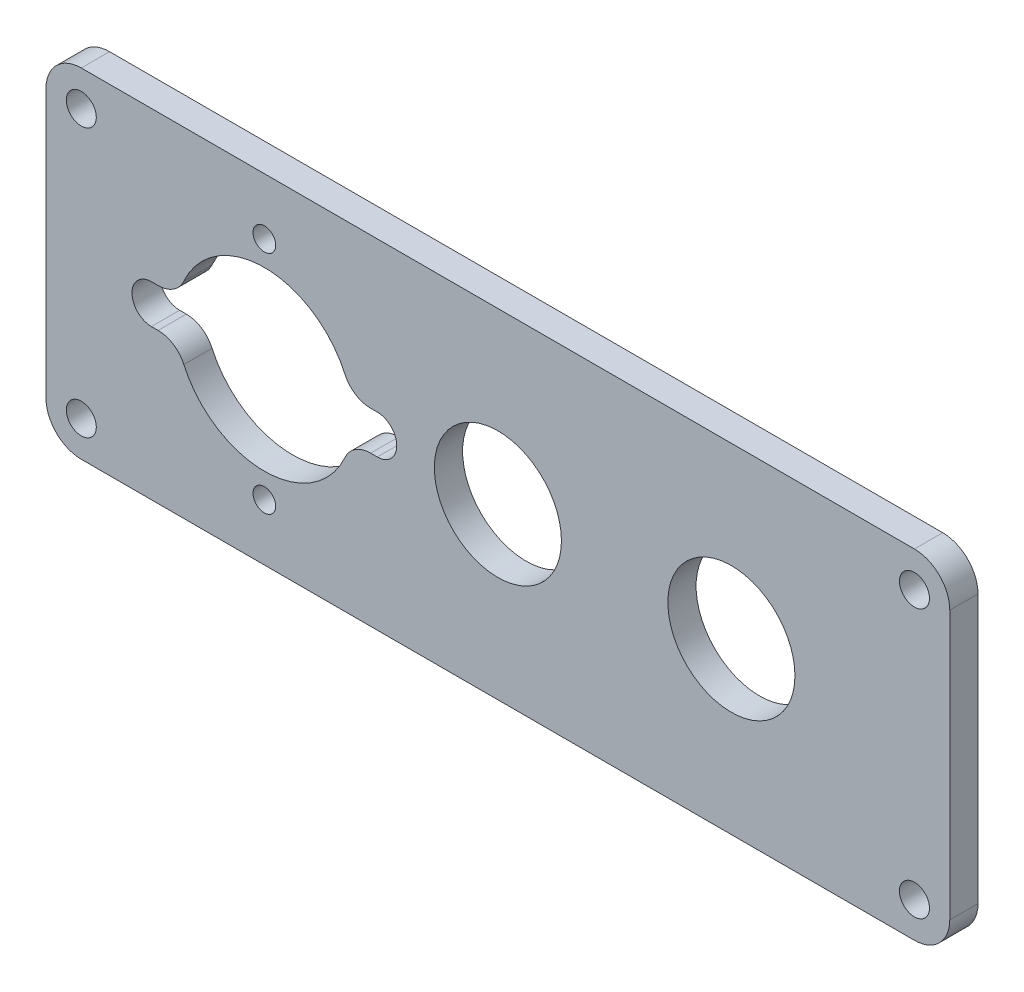
SolidWorks part; units mm, degrees
ref_plane "Front Plane" through (0, 0, 0) normal (0, 0, 1) x (1, 0, 0)
ref_plane "Top Plane" through (0, 0, 0) normal (0, 1, 0) x (1, 0, 0)
ref_plane "Right Plane" through (0, 0, 0) normal (1, 0, 0) x (0, 0, -1)
sketch "Sketch1" plane through (0, 0, 0) normal (0, 0, 1) x (1, 0, 0)
  line L0 (-28.6016, 4.3688) -> (-27.1018, 4.3688)
  line L1 (-93.6625, -38.1) -> (93.6625, -38.1)
  line L2 (-101.6, -30.1625) -> (-101.6, 30.1625)
  line L3 (-93.6625, 38.1) -> (93.6625, 38.1)
  line L4 (101.6, -30.1625) -> (101.6, 30.1625)
  line L5 (-101.6, -38.1) -> (101.6, 38.1) construction
  line L6 (-101.6, 38.1) -> (101.6, -38.1) construction
  line L7 (-93.6625, -30.1625) -> (93.6625, -30.1625) construction
  line L8 (-93.6625, -30.1625) -> (-93.6625, 30.1625) construction
  line L9 (-93.6625, 30.1625) -> (93.6625, 30.1625) construction
  line L10 (93.6625, -30.1625) -> (93.6625, 30.1625) construction
  line L11 (-93.6625, -30.1625) -> (93.6625, 30.1625) construction
  line L12 (-93.6625, 30.1625) -> (93.6625, -30.1625) construction
  line L13 (-77.9018, 0) -> (-52.5018, -25.4) construction
  line L14 (-77.9018, 0) -> (-52.5018, 25.4) construction
  line L15 (-52.5018, 25.4) -> (-27.1018, 0) construction
  line L16 (-52.5018, -25.4) -> (-27.1018, 0) construction
  line L17 (-77.9018, 0) -> (-27.1018, 0) construction
  line L18 (-52.5018, 25.4) -> (-52.5018, -25.4) construction
  line L19 (-27.1018, -4.3688) -> (-28.6016, -4.3688)
  line L20 (-76.402, 4.3688) -> (-77.9018, 4.3688)
  line L21 (-76.402, -4.3688) -> (-77.9018, -4.3688)
  circle A0 centre (0, 0) radius 14.2875
  circle A1 centre (52.5018, 0) radius 14.2875
  circle A2 centre (-52.5018, 0) radius 14.2875 construction
  circle A3 centre (-93.6625, 30.1625) radius 3.3734
  circle A4 centre (93.6625, 30.1625) radius 3.3734
  circle A5 centre (93.6625, -30.1625) radius 3.3734
  circle A6 centre (-93.6625, -30.1625) radius 3.3734
  arc A7 (-93.6625, -38.1) -> (-101.6, -30.1625) centre (-93.6625, -30.1625) cw
  arc A8 (93.6625, -38.1) -> (101.6, -30.1625) centre (93.6625, -30.1625) ccw
  arc A9 (93.6625, 38.1) -> (101.6, 30.1625) centre (93.6625, 30.1625) cw
  arc A10 (-101.6, 30.1625) -> (-93.6625, 38.1) centre (-93.6625, 30.1625) cw
  arc A11 (-34.3956, 8.1203) -> (-70.608, 8.1203) centre (-52.5018, 0) ccw
  circle A12 centre (-52.5018, 25.4) radius 2.5527
  arc A13 (-27.1018, -4.3688) -> (-27.1018, 4.3688) centre (-27.1018, 0) ccw
  circle A14 centre (-52.5018, -25.4) radius 2.5527
  arc A15 (-77.9018, 4.3688) -> (-77.9018, -4.3688) centre (-77.9018, 0) ccw
  arc A16 (-28.6016, -4.3688) -> (-34.3956, -8.1203) centre (-28.6016, -10.7188) ccw
  arc A17 (-28.6016, 4.3688) -> (-34.3956, 8.1203) centre (-28.6016, 10.7188) cw
  arc A18 (-70.608, -8.1203) -> (-34.3956, -8.1203) centre (-52.5018, 0) ccw
  arc A19 (-76.402, -4.3688) -> (-70.608, -8.1203) centre (-76.402, -10.7188) cw
  arc A20 (-76.402, 4.3688) -> (-70.608, 8.1203) centre (-76.402, 10.7188) ccw
  point P51 (-71.8587, -4.3688)
  dimension "D3" = 28.575
  dimension "D8" = 6.7469
  dimension "D9" = 7.9375
  dimension "D10" = 39.6875
  dimension "D11" = 8.7376
  dimension "D12" = 5.1054
  dimension "D14" = 6.35
  dimension "D15" = 6.35
  dimension "D2" = 52.5018
  dimension "D1" = 52.5018
  dimension "D4" = 187.325
  dimension "D5" = 60.325
  dimension "D6" = 76.2
  dimension "D7" = 203.2
  dimension "D13" = 50.8
extrude "Boss-Extrude1" add sketch "Sketch1" along normal blind 6.35
equation "\"D1@Sketch1\"=\"D2@Sketch1\""
